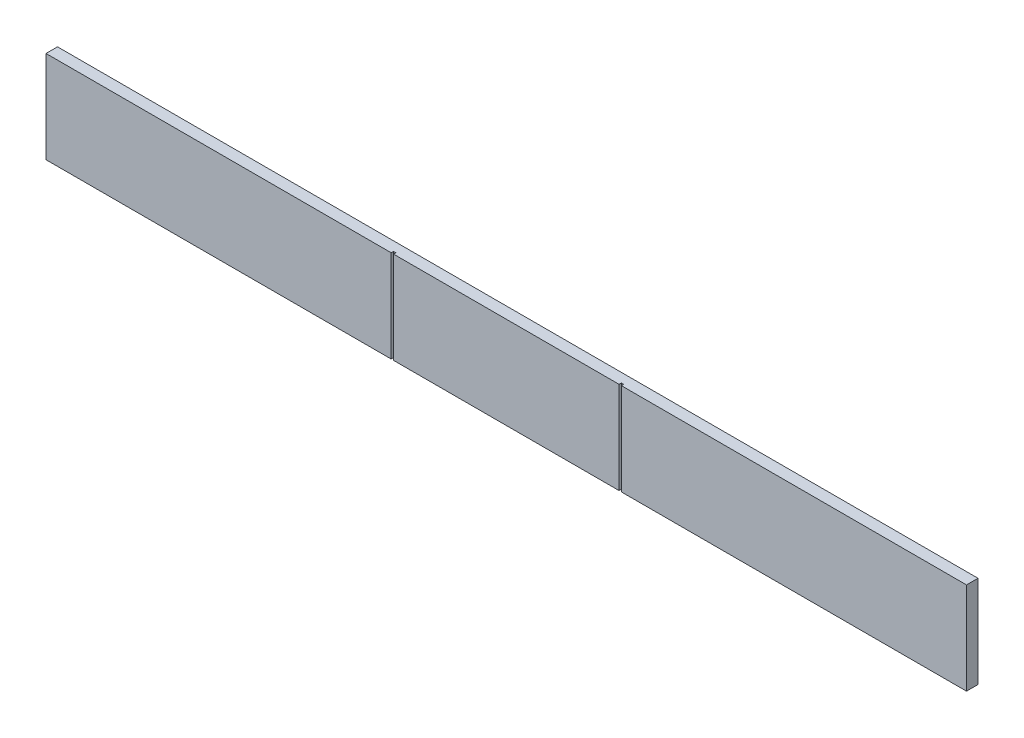
SolidWorks part; units mm, degrees
ref_plane "Front Plane" through (0, 0, 0) normal (0, 0, 1) x (1, 0, 0)
ref_plane "Top Plane" through (0, 0, 0) normal (0, 1, 0) x (1, 0, 0)
ref_plane "Right Plane" through (0, 0, 0) normal (1, 0, 0) x (0, 0, -1)
sketch "Sketch1" plane through (0, 0, 0) normal (0, 0, 1) x (1, 0, 0)
  line L1 (-254, -25.4) -> (254, -25.4)
  line L2 (-254, -25.4) -> (-254, 25.4)
  line L3 (-254, 25.4) -> (254, 25.4)
  line L4 (254, -25.4) -> (254, 25.4)
  line L5 (-254, -25.4) -> (254, 25.4) construction
  line L6 (-254, 25.4) -> (254, -25.4) construction
  point P0 (0, 0)
  dimension "D1" = 50.8
  dimension "D2" = 508
extrude "Boss-Extrude1" add sketch "Sketch1" along normal blind 6.35
sketch "Sketch2" plane through (0, 0, 6.35) normal (0, 0, 1) x (1, 0, 0)
  line L0 (254, -25.4) -> (254, 25.4) construction
  line L1 (254, 25.4) -> (-254, 25.4) construction
  line L2 (-254, -25.4) -> (254, -25.4) construction
  line L3 (-63.5, 25.4) -> (-62.23, 25.4)
  line L4 (62.23, 25.4) -> (63.5, 25.4)
  line L7 (-63.5, 25.4) -> (-63.5, -25.4)
  line L8 (-63.5, -25.4) -> (-62.23, -25.4)
  line L9 (-62.23, 25.4) -> (-62.23, -25.4)
  line L10 (62.23, 25.4) -> (62.23, -25.4)
  line L11 (62.23, -25.4) -> (63.5, -25.4)
  line L12 (63.5, 25.4) -> (63.5, -25.4)
  line L13 (-254, 25.4) -> (-254, -25.4) construction
  dimension "D1" = 1.27
  dimension "D2" = 1.27
  dimension "D3" = 190.5
  dimension "D4" = 190.5
extrude "Cut-Extrude1" cut sketch "Sketch2" against normal blind 1.27
